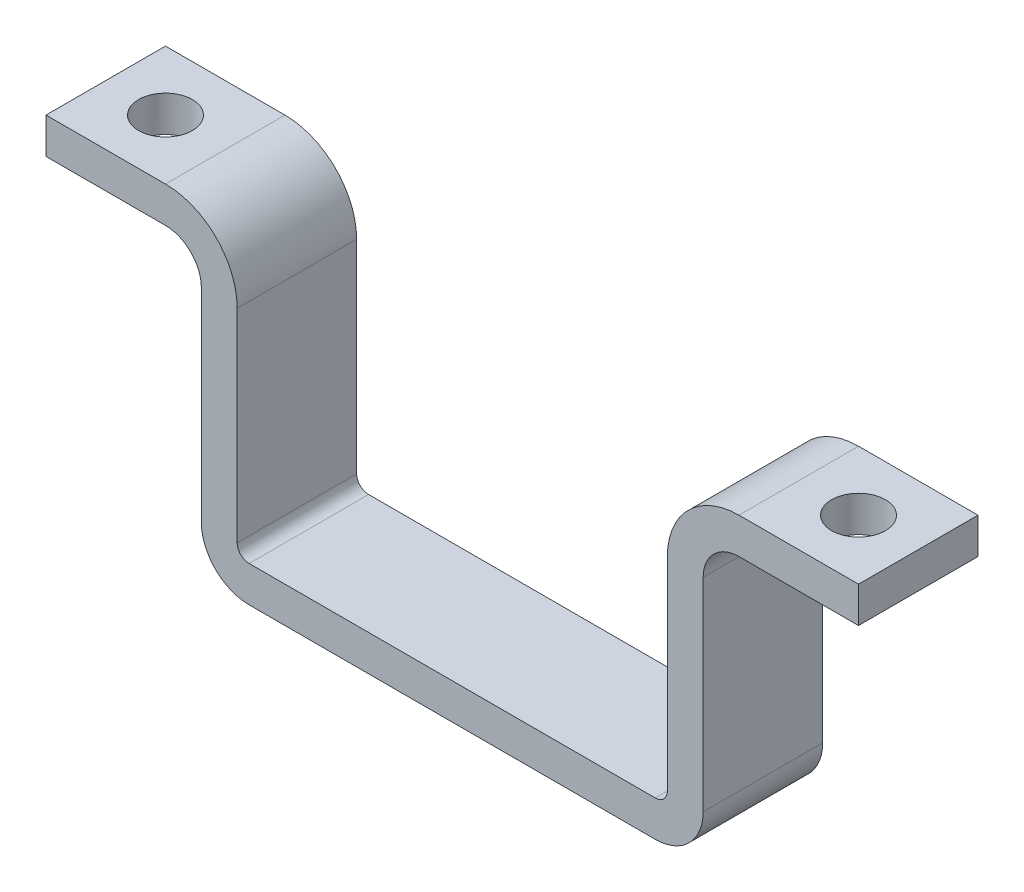
SolidWorks part; units mm, degrees
ref_plane "Front Plane" through (0, 0, 0) normal (0, 0, 1) x (1, 0, 0)
ref_plane "Top Plane" through (0, 0, 0) normal (0, 1, 0) x (1, 0, 0)
ref_plane "Right Plane" through (0, 0, 0) normal (1, 0, 0) x (0, 0, -1)
sketch "Sketch1" plane through (0, 0, 0) normal (0, 0, 1) x (1, 0, 0)
  line L0 (-17, 0) -> (17, 0)
  line L1 (18, 1) -> (18, 18)
  line L2 (24, 24) -> (34, 24)
  line L3 (-18, 1) -> (-18, 18)
  line L4 (-24, 24) -> (-34, 24)
  line L5 (24, 21) -> (34, 21)
  line L6 (21, 1) -> (21, 18)
  line L7 (-17, -3) -> (17, -3)
  line L8 (-21, 1) -> (-21, 18)
  line L9 (-24, 21) -> (-34, 21)
  line L10 (-24, 24) -> (-34, 24) construction
  line L11 (-34, 24) -> (-34, 21)
  line L12 (34, 24) -> (34, 21)
  arc A0 (-18, 18) -> (-24, 24) centre (-24, 18) ccw
  arc A1 (18, 18) -> (24, 24) centre (24, 18) cw
  arc A2 (17, 0) -> (18, 1) centre (17, 1) ccw
  arc A3 (-17, 0) -> (-18, 1) centre (-17, 1) cw
  arc A4 (21, 18) -> (24, 21) centre (24, 18) cw
  arc A5 (17, -3) -> (21, 1) centre (17, 1) ccw
  arc A6 (-17, -3) -> (-21, 1) centre (-17, 1) cw
  arc A7 (-21, 18) -> (-24, 21) centre (-24, 18) ccw
  point P4 (0, 0)
  point P14 (18, 0)
  point P17 (-18, 0)
  dimension "D2" = 6
  dimension "D3" = 6
  dimension "D4" = 1
  dimension "D1" = 34
  dimension "D6" = 10
  dimension "D7" = 24
  dimension "D5" = 3
extrude "Boss-Extrude1" add sketch "Sketch1" along normal mid plane 10 contours L4 L11 L9 A7 L8 A6 L7 A5 L6 A4 L5 L12 L2 A1 L1 A2 L0 A3 L3 A0
sketch "Sketch2" plane through (0, 24, 0) normal (0, 1, 0) x (1, 0, 0)
  line L0 (-34, -5) -> (-34, 5) construction
  line L1 (-24, 5) -> (-34, 5) construction
  circle A0 centre (-29, 0) radius 2.25
  point P2 (0, 0)
  point P5 (-34, 0)
  point P8 (-29, 5)
  dimension "D1" = 4.5
extrude "Cut-Extrude1" cut sketch "Sketch2" against normal through all
mirror "Mirror1" about plane through (0, 0, 0) normal (1, 0, 0) of "Cut-Extrude1"
